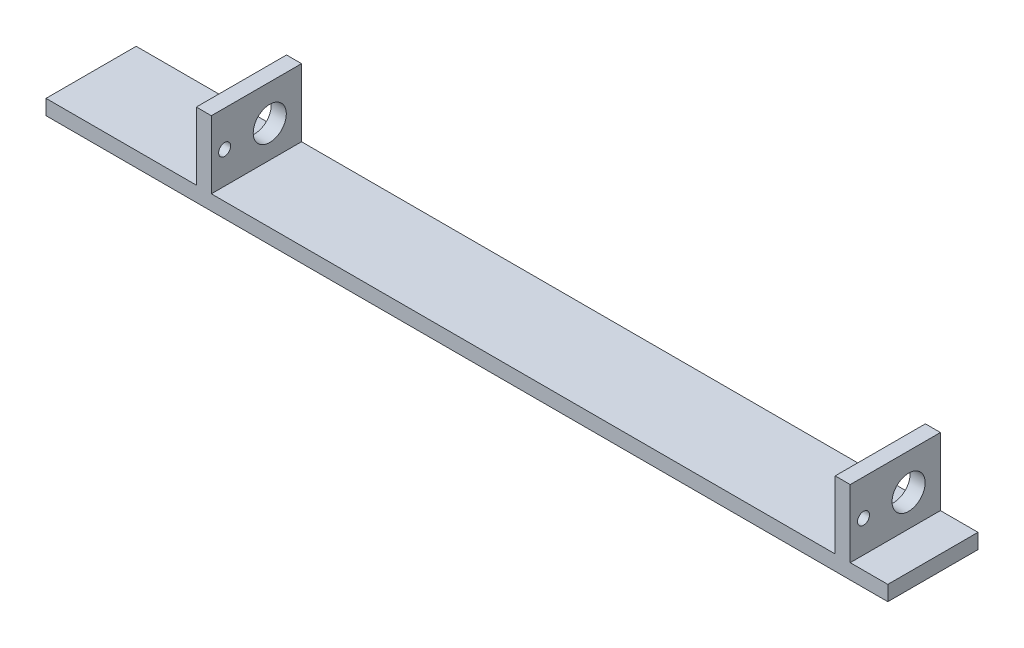
SolidWorks part; units mm, degrees
ref_plane "Front Plane" through (0, 0, 0) normal (0, 0, 1) x (1, 0, 0)
ref_plane "Top Plane" through (0, 0, 0) normal (0, 1, 0) x (1, 0, 0)
ref_plane "Right Plane" through (0, 0, 0) normal (1, 0, 0) x (0, 0, -1)
sketch "Sketch1" plane through (0, 0, 0) normal (0, 1, 0) x (1, 0, 0)
  line L1 (-280, 30) -> (280, 30)
  line L2 (-280, 30) -> (-280, -30)
  line L3 (-280, -30) -> (280, -30)
  line L4 (280, 30) -> (280, -30)
  line L5 (-280, 30) -> (280, -30) construction
  line L6 (-280, -30) -> (280, 30) construction
  point P0 (0, 0)
  dimension "D1" = 60
  dimension "D2" = 560
extrude "Boss-Extrude1" add sketch "Sketch1" along normal blind 10
sketch "Sketch2" plane through (0, 10, 0) normal (0, 1, 0) x (1, 0, 0)
  line L1 (280, 30) -> (-280, 30) construction
  line L2 (-180, 30) -> (-180, -30)
  line L3 (-280, -30) -> (280, -30) construction
  line L4 (-180, -30) -> (-170, -30)
  line L5 (-170, -30) -> (-170, 30)
  line L6 (-170, 30) -> (-180, 30)
  line L8 (255, 30) -> (255, -30)
  line L9 (255, -30) -> (245, -30)
  line L10 (245, -30) -> (245, 30)
  line L11 (245, 30) -> (255, 30)
  dimension "D3" = 10
  dimension "D4" = 10
extrude "Boss-Extrude2" add sketch "Sketch2" along normal blind 45
sketch "Sketch3" plane through (-180, 0, 0) normal (-1, 0, 0) x (0, 0, 1)
  circle A0 centre (-8.85, 31.15) radius 11
  circle A1 centre (21.15, 31.15) radius 4
  dimension "D4" = 22
  dimension "D5" = 8
  dimension "D3" = 30
extrude "Cut-Extrude1" cut sketch "Sketch3" against normal blind 440
sketch "Sketch4" plane through (0, 0, 0) normal (0, -1, 0) x (1, 0, 0)
  line L0 (-280, -30) -> (-280, 30) construction
  line L1 (-180, -30) -> (-280, -30) construction
  line L2 (-280, 30) -> (280, 30) construction
  line L3 (280, 30) -> (280, -30) construction
  circle A0 centre (-270, 0) radius 5
  circle A1 centre (260, 0) radius 5
  dimension "D1" = 10
  dimension "D3" = 30
  dimension "D5" = 10
  dimension "D2" = 10
  dimension "D4" = 30
  dimension "D6" = 20
extrude "Boss-Extrude3" add sketch "Sketch4" along normal blind 10
